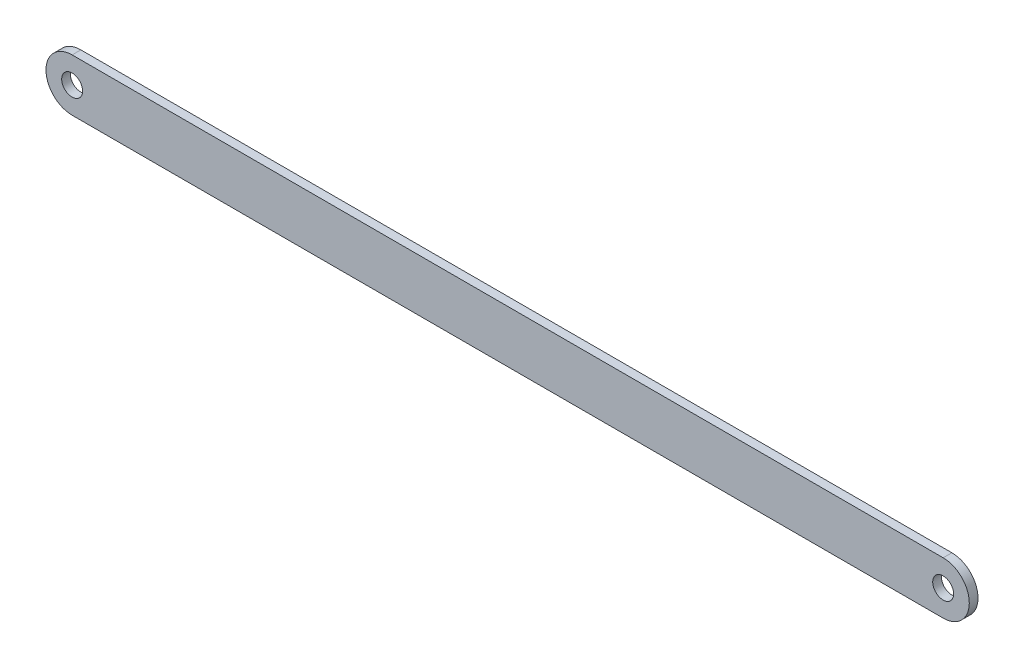
SolidWorks part; units mm, degrees
ref_plane "Front Plane" through (0, 0, 0) normal (0, 0, 1) x (1, 0, 0)
ref_plane "Top Plane" through (0, 0, 0) normal (0, 1, 0) x (1, 0, 0)
ref_plane "Right Plane" through (0, 0, 0) normal (1, 0, 0) x (0, 0, -1)
sketch "Sketch1" plane through (0, 0, 0) normal (0, 0, 1) x (1, 0, 0)
  line L0 (120, -126) -> (620, -126) construction
  line L1 (120, -111) -> (620, -111)
  line L2 (120, -141) -> (620, -141)
  arc A0 (120, -111) -> (120, -141) centre (120, -126) ccw
  arc A1 (620, -141) -> (620, -111) centre (620, -126) ccw
  circle A3 centre (120, -126) radius 6
  circle A4 centre (620, -126) radius 6
  circle A5 centre (120, -126) radius 6 construction
  point P3 (370, -126)
  dimension "D1" = 30
  dimension "D2" = 500
extrude "Boss-Extrude1" add sketch "Sketch1" along normal blind 5
